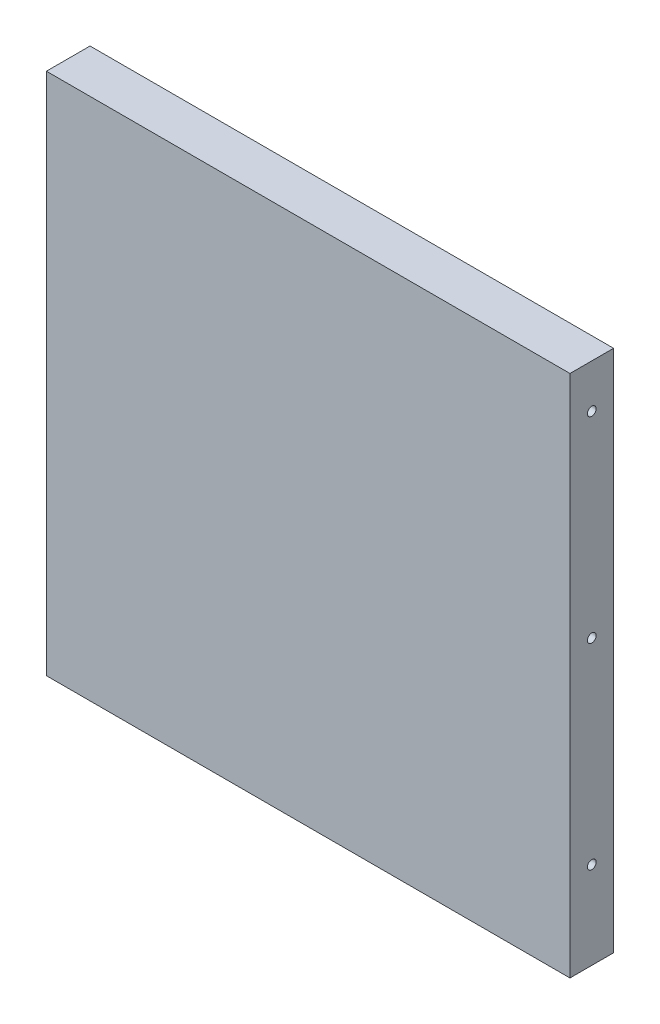
SolidWorks part; units mm, degrees
ref_plane "Front" through (0, 0, 0) normal (0, 0, 1) x (1, 0, 0)
ref_plane "Top" through (0, 0, 0) normal (0, 1, 0) x (1, 0, 0)
ref_plane "Right" through (0, 0, 0) normal (1, 0, 0) x (0, 0, -1)
sketch "Sketch1" plane through (0, 0, 0) normal (0, 1, 0) x (1, 0, 0)
  line L1 (-152.4, -12.7) -> (152.4, -12.7)
  line L2 (-152.4, -12.7) -> (-152.4, 12.7)
  line L3 (-152.4, 12.7) -> (152.4, 12.7)
  line L4 (152.4, -12.7) -> (152.4, 12.7)
  line L5 (-152.4, -12.7) -> (152.4, 12.7) construction
  line L6 (-152.4, 12.7) -> (152.4, -12.7) construction
  point P0 (0, 0)
  dimension "D1" = 25.4
  dimension "D2" = 304.8
extrude "Boss-Extrude1" add sketch "Sketch1" along normal mid plane 304.8
sketch "Sketch2" plane through (152.4, 0, 0) normal (1, 0, 0) x (0, 0, -1)
  point P0 (0, 127)
  point P1 (0, 12.7)
  point P3 (0, -101.6)
hole_wizard "1/4-20 Tapped Hole1" positions "Sketch3" profile "Sketch5" tap size "1/4-20" standard "ANSI Inch"
sketch "Sketch3" plane through (152.4, 0, 0) normal (1, 0, 0) x (0, 0, -1)
  point P0 (0, 127)
  point P3 (0, 12.7)
  point P6 (0, -101.6)
cosmetic thread "Hole Thread1" parameters "D2"=6.35
cosmetic thread "Hole Thread2" parameters "D2"=6.35
cosmetic thread "Hole Thread3" parameters "D2"=6.35
sketch "Sketch5" plane through (152.4, 127, 0) normal (0, 1, 0) x (0, 0, -1)
  line L0 (0, 0) -> (0, 30.7438)
  line L1 (0, 30.7438) -> (2.5527, 29.21)
  line L2 (2.5527, 29.21) -> (2.5527, 0)
  line L5 (2.5527, 0) -> (0, 0)
  line L10 (0, 30.7438) -> (-2.5527, 29.21) construction
  line L11 (0, -6.35) -> (0, 107.95) construction
  dimension "Tap Drill Dia." = 5.1054
  dimension "Tap Drill Depth" = 29.21
  dimension "Drill Angle" = 118
mirror "Mirror1" about plane through (0, 0, 0) normal (1, 0, 0) of "1/4-20 Tapped Hole1"
cosmetic thread "Hole Thread4" parameters "D1"=304.8, "D2"=6.35
cosmetic thread "Hole Thread5" parameters "D1"=304.8, "D2"=6.35
cosmetic thread "Hole Thread6" parameters "D1"=304.8, "D2"=6.35
